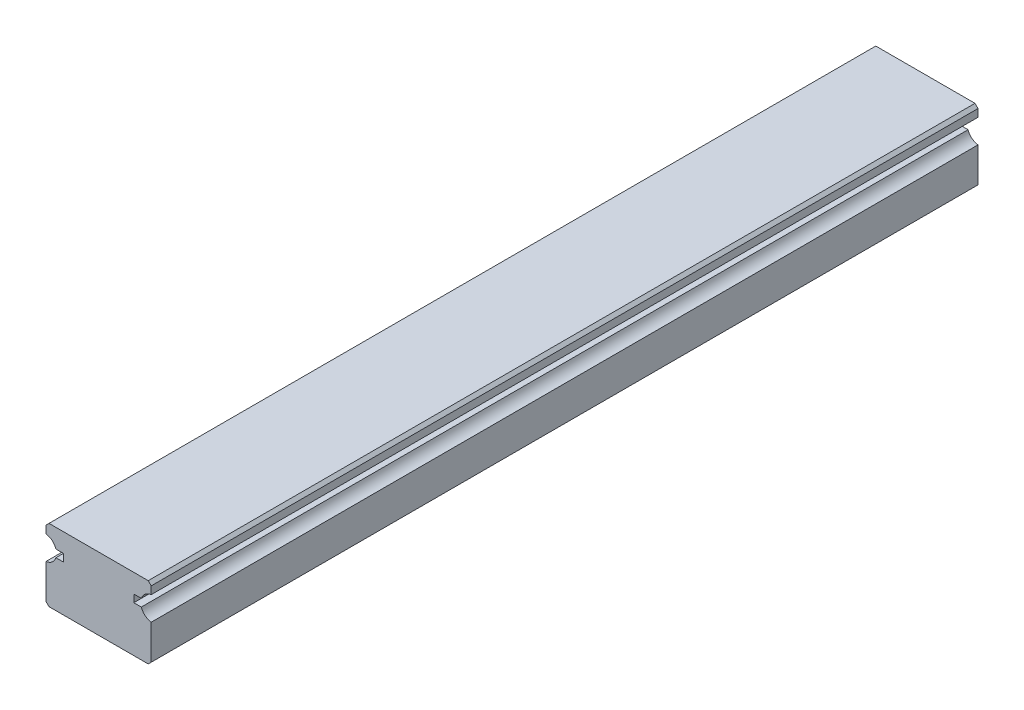
SolidWorks part; units mm, degrees
ref_plane "Спереди" through (0, 0, 0) normal (0, 0, 1) x (1, 0, 0)
ref_plane "Сверху" through (0, 0, 0) normal (0, 1, 0) x (1, 0, 0)
ref_plane "Справа" through (0, 0, 0) normal (1, 0, 0) x (0, 0, -1)
sketch "Sketch1" plane through (0, 0, 0) normal (0, 0, 1) x (1, 0, 0)
  line L0 (0, 0) -> (0, 4.3706) construction
  line L1 (-3.3, -2.4) -> (3.3, -2.4)
  line L2 (-3.5, -2.2) -> (-3.5, 0.1063)
  line L3 (-3.3, 2.4) -> (3.3, 2.4)
  line L4 (3.5, -2.2) -> (3.5, 0.1063)
  line L5 (-3.5, -2.4) -> (3.5, 2.4) construction
  line L6 (-3.5, 2.4) -> (3.5, -2.4) construction
  line L7 (-3.5, 1.6937) -> (-3.5, 2.2)
  line L8 (3.5, 1.6937) -> (3.5, 2.2)
  line L9 (-3.5, -2.2) -> (-3.3, -2.4)
  line L10 (3.3, -2.4) -> (3.5, -2.2)
  line L11 (3.3, 2.4) -> (3.5, 2.2)
  line L12 (-3.5, 2.2) -> (-3.3, 2.4)
  line L13 (2.8401, 0.65) -> (2.3401, 0.65)
  line L14 (-2.8401, 0.65) -> (-2.3401, 0.65)
  line L15 (2.3401, 0.65) -> (2.3401, 1.15)
  line L16 (-2.8401, 1.15) -> (-2.3401, 1.15)
  line L17 (-2.3401, 0.65) -> (-2.3401, 1.15)
  line L18 (2.8401, 1.15) -> (2.3401, 1.15)
  arc A0 (-3.5, 1.6937) -> (-2.8401, 1.15) centre (-3.6, 0.9) cw
  arc A1 (3.5, 1.6937) -> (2.8401, 1.15) centre (3.6, 0.9) ccw
  arc A2 (-2.8401, 0.65) -> (-3.5, 0.1063) centre (-3.6, 0.9) cw
  arc A3 (2.8401, 0.65) -> (3.5, 0.1063) centre (3.6, 0.9) ccw
  point P0 (0, 0)
  dimension "D4" = 0.8
  dimension "D5" = 0.1
  dimension "D1" = 7
  dimension "D2" = 4.8
  dimension "D3" = 1.5
  dimension "D6" = 0.5
  dimension "D7" = 0.5
extrude "Extrude1" add sketch "Sketch1" along normal mid plane 55
